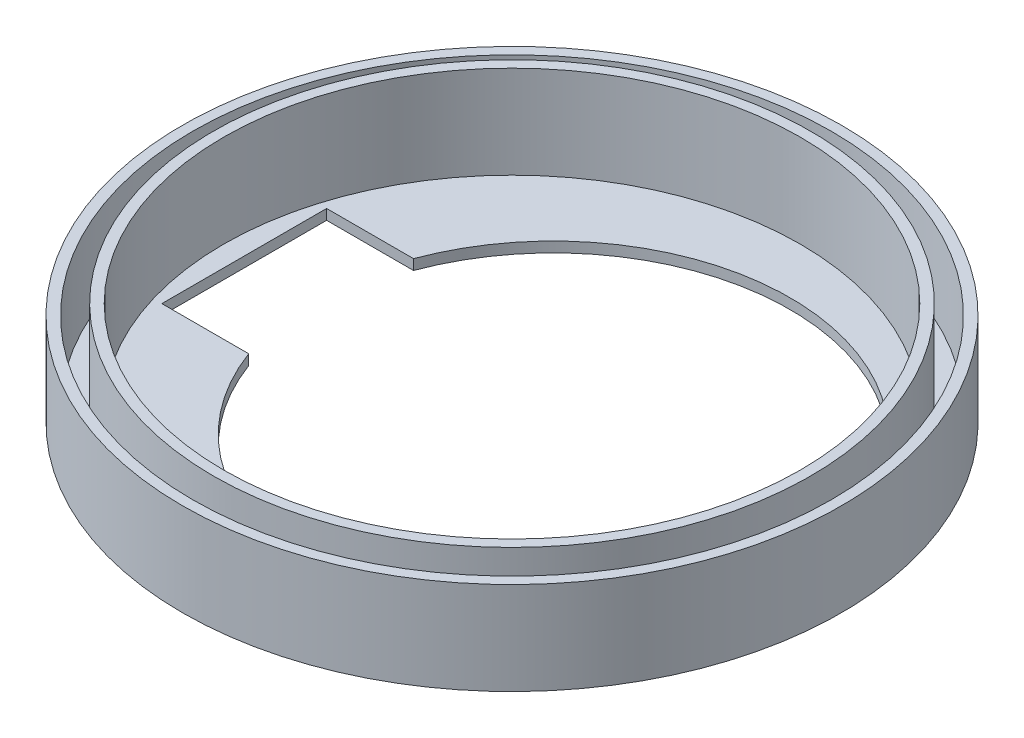
SolidWorks part; units mm, degrees
ref_plane "Front Plane" through (0, 0, 0) normal (0, 0, 1) x (1, 0, 0)
ref_plane "Top Plane" through (0, 0, 0) normal (0, 1, 0) x (1, 0, 0)
ref_plane "Right Plane" through (0, 0, 0) normal (1, 0, 0) x (0, 0, -1)
sketch "Sketch1" plane through (0, 0, 0) normal (0, 1, 0) x (1, 0, 0)
  circle A0 centre (0, 0) radius 16
extrude "Boss-Extrude1" add sketch "Sketch1" along normal blind 0.5
sketch "Sketch2" plane through (0, 0.5, 0) normal (0, 1, 0) x (1, 0, 0)
  circle A0 centre (2, 0) radius 11.5
extrude "Cut-Extrude1" cut sketch "Sketch2" against normal blind 0.5
sketch "Sketch3" plane through (0, 0, 0) normal (0, 1, 0) x (1, 0, 0)
  line L1 (2, 4) -> (-13, 4)
  line L2 (2, 4) -> (2, -4)
  line L3 (2, -4) -> (-13, -4)
  line L4 (-13, 4) -> (-13, -4)
extrude "Cut-Extrude4" cut sketch "Sketch3" along normal blind 2.5
sketch "Sketch4" plane through (0, 0, 0) normal (0, 1, 0) x (1, 0, 0)
  circle A0 centre (0, 0) radius 16
  circle A1 centre (0, 0) radius 15.5
extrude "Boss-Extrude2" add sketch "Sketch4" along normal blind 4.5
sketch "Sketch5" plane through (0, 0.5, 0) normal (0, 1, 0) x (1, 0, 0)
  circle A0 centre (0, 0) radius 14.5
  circle A1 centre (0, 0) radius 14.5
  circle A2 centre (0, 0) radius 14
extrude "Boss-Extrude3" add sketch "Sketch5" along normal blind 4.5 contours A0 | A2
